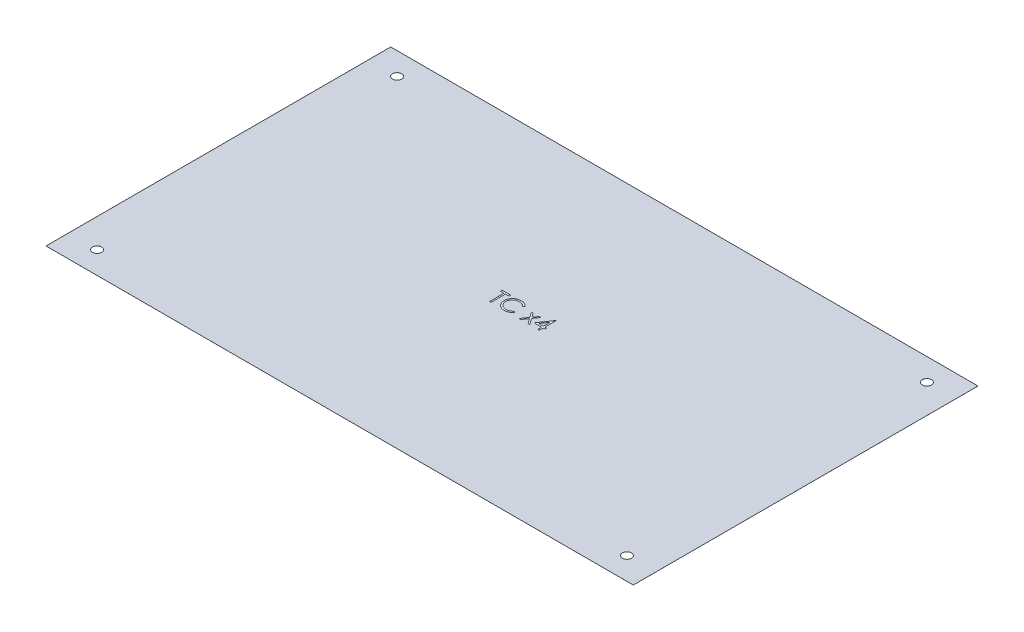
SolidWorks part; units mm, degrees
ref_plane "Front Plane" through (0, 0, 0) normal (0, 0, 1) x (1, 0, 0)
ref_plane "Top Plane" through (0, 0, 0) normal (0, 1, 0) x (1, 0, 0)
ref_plane "Right Plane" through (0, 0, 0) normal (1, 0, 0) x (0, 0, -1)
sketch "Sketch2" plane through (0, 0, 0) normal (0, 1, 0) x (1, 0, 0)
  line L1 (-116.84, -68.58) -> (116.84, -68.58)
  line L2 (-116.84, -68.58) -> (-116.84, 68.58)
  line L3 (-116.84, 68.58) -> (116.84, 68.58)
  line L4 (116.84, -68.58) -> (116.84, 68.58)
  line L5 (-116.84, -68.58) -> (116.84, 68.58) construction
  line L6 (-116.84, 68.58) -> (116.84, -68.58) construction
  point P0 (0, 0)
  dimension "D1" = 137.16
  dimension "D2" = 233.68
extrude "Boss-Extrude1" add sketch "Sketch2" along normal blind 0.0025
sketch "Sketch3" plane through (0, 0.0025, 0) normal (0, 1, 0) x (1, 0, 0)
  line L1 (-105.41, -59.69) -> (105.41, -59.69)
  line L2 (-105.41, -59.69) -> (-105.41, 59.69)
  line L3 (-105.41, 59.69) -> (105.41, 59.69)
  line L4 (105.41, -59.69) -> (105.41, 59.69)
  line L5 (-105.41, -59.69) -> (105.41, 59.69) construction
  line L6 (-105.41, 59.69) -> (105.41, -59.69) construction
  circle A0 centre (-105.41, 59.69) radius 1.8288
  circle A7 centre (105.41, 59.69) radius 1.8288
  circle A8 centre (105.41, -59.69) radius 1.8288
  circle A9 centre (-105.41, -59.69) radius 1.8288
  point P0 (0, 0)
  dimension "D3" = 3.6576
  dimension "D1" = 119.38
  dimension "D2" = 210.82
  dimension "D4" = 2
  dimension "D5" = 2
extrude "Cut-Extrude1" cut sketch "Sketch3" against normal through all contours A9 | A8 | A7 | A0
sketch "Sketch5" plane through (0, 0.0025, 0) normal (0, 1, 0) x (1, 0, 0)
  text T0 "TC x4\r\n" font "Century Gothic" height 6.35
  point P1 (-23.0976, -2.5229)
extrude "Cut-Extrude2" cut sketch "Sketch5" against normal blind 2.54
